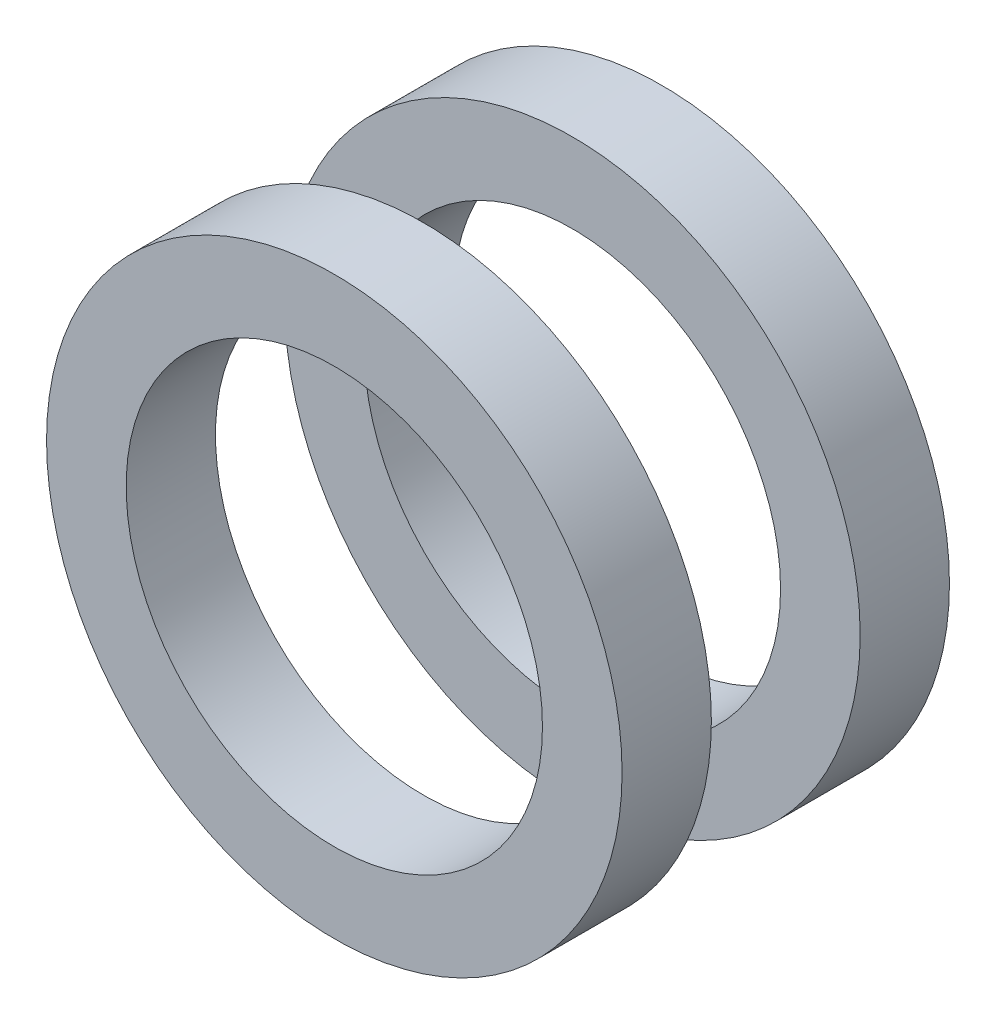
SolidWorks part; units mm, degrees
ref_plane "Спереди" through (0, 0, 0) normal (0, 0, 1) x (1, 0, 0)
ref_plane "Сверху" through (0, 0, 0) normal (0, 1, 0) x (1, 0, 0)
ref_plane "Справа" through (0, 0, 0) normal (1, 0, 0) x (0, 0, -1)
sketch "Эскиз1" plane through (0, 0, 0) normal (0, 0, 1) x (1, 0, 0)
  circle A0 centre (0, 0) radius 58.0154
  circle A1 centre (0, 0) radius 41.9615
extrude "Endturn_R" add sketch "Эскиз1" along normal blind 18 from offset 15 separate body
sketch "Эскиз2" plane through (0, 0, 0) normal (0, 0, 1) x (1, 0, 0)
  circle A0 centre (0, 0) radius 58.0154
  circle A1 centre (0, 0) radius 41.9615
extrude "Endturn_L" add sketch "Эскиз2" along normal blind 18 from offset 33 separate body
